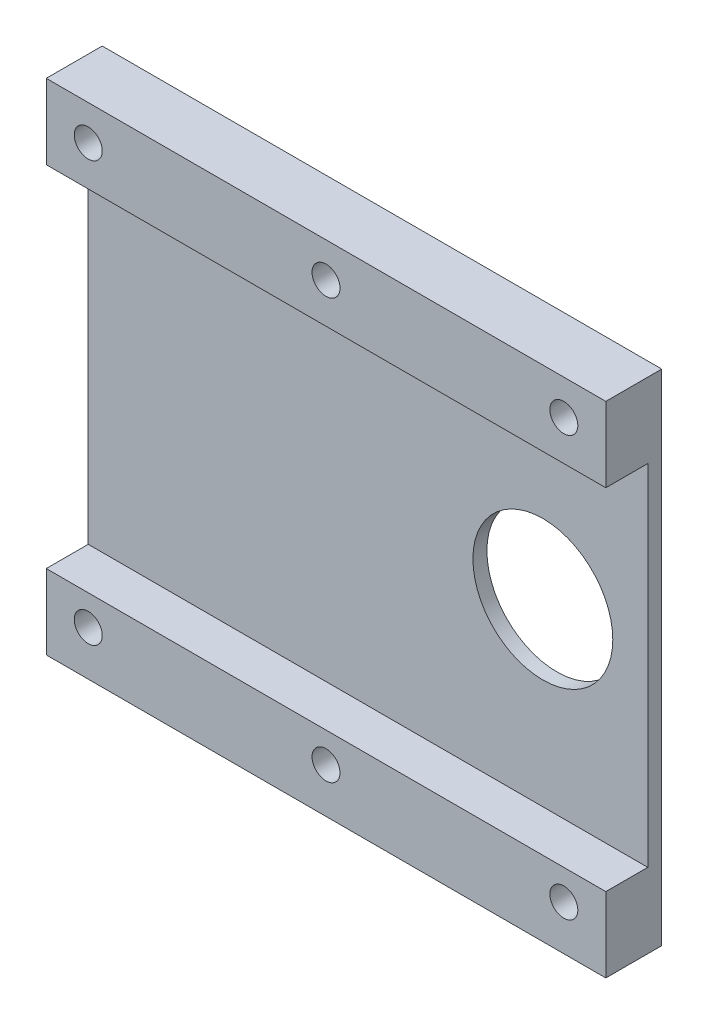
SolidWorks part; units mm, degrees
ref_plane "Front Plane" through (0, 0, 0) normal (0, 0, 1) x (1, 0, 0)
ref_plane "Top Plane" through (0, 0, 0) normal (0, 1, 0) x (1, 0, 0)
ref_plane "Right Plane" through (0, 0, 0) normal (1, 0, 0) x (0, 0, -1)
sketch "Sketch1" plane through (0, 0, 0) normal (0, 0, 1) x (1, 0, 0)
  line L0 (0, 17.85) -> (0, -17.85) construction
  line L1 (-20, 17.85) -> (20, 17.85)
  line L2 (-20, 17.85) -> (-20, -17.85)
  line L3 (-20, -17.85) -> (20, -17.85)
  line L4 (20, 17.85) -> (20, -17.85)
  line L5 (-20, 17.85) -> (20, -17.85) construction
  line L6 (-20, -17.85) -> (20, 17.85) construction
  circle A0 centre (-17, 15.35) radius 1
  circle A1 centre (0, 15.35) radius 1
  circle A2 centre (17, 15.35) radius 1
  circle A3 centre (-17, -14.65) radius 1
  circle A4 centre (0, -14.65) radius 1
  circle A5 centre (17, -14.65) radius 1
  point P0 (0, 0)
  dimension "D5" = 2
  dimension "D6" = 2
  dimension "D7" = 2
  dimension "D10" = 2
  dimension "D11" = 2
  dimension "D12" = 2
  dimension "D1" = 40
  dimension "D2" = 35.7
  dimension "D3" = 17
  dimension "D4" = 17
  dimension "D8" = 30
  dimension "D9" = 2.5
extrude "Boss-Extrude1" add sketch "Sketch1" along normal blind 4
sketch "Sketch2" plane through (0, 0, 4) normal (0, 0, 1) x (1, 0, 0)
  line L1 (-25, 12.5) -> (25, 12.5)
  line L2 (-25, 12.5) -> (-25, -12.5)
  line L3 (-25, -12.5) -> (25, -12.5)
  line L4 (25, 12.5) -> (25, -12.5)
  line L5 (-25, 12.5) -> (25, -12.5) construction
  line L6 (-25, -12.5) -> (25, 12.5) construction
  point P0 (0, 0)
  dimension "D1" = 25
  dimension "D2" = 50
extrude "Cut-Extrude1" cut sketch "Sketch2" against normal blind 3
sketch "Sketch3" plane through (0, -17.85, 0) normal (0, -1, 0) x (1, 0, 0)
  line L0 (-20, 2) -> (20, 2) construction
  line L1 (-20, 4) -> (-20, 0) construction
  line L2 (20, 4) -> (20, 0) construction
  line L3 (-7.5, 2) -> (7.5, 2) construction
  line L4 (0, 4) -> (0, 0) construction
  line L5 (-20, 4) -> (20, 4) construction
  circle A0 centre (-7.5, 2) radius 1
  circle A1 centre (7.5, 2) radius 1
  point P15 (7.981, 2.5)
  point P16 (-6.8493, 2.5)
  point P17 (-7.0123, 7.5816)
  point P18 (0, 2)
  point P19 (-7.5, 2.5)
  dimension "D1" = 2
  dimension "D2" = 2
  dimension "D3" = 15
extrude "Cut-Extrude2" cut sketch "Sketch3" against normal blind 3
sketch "Sketch4" plane through (0, 0, 0) normal (0, 0, -1) x (-1, 0, 0)
  circle A0 centre (-12.5, 0.35) radius 5
  dimension "D1" = 10
extrude "Cut-Extrude3" cut sketch "Sketch4" against normal through all
